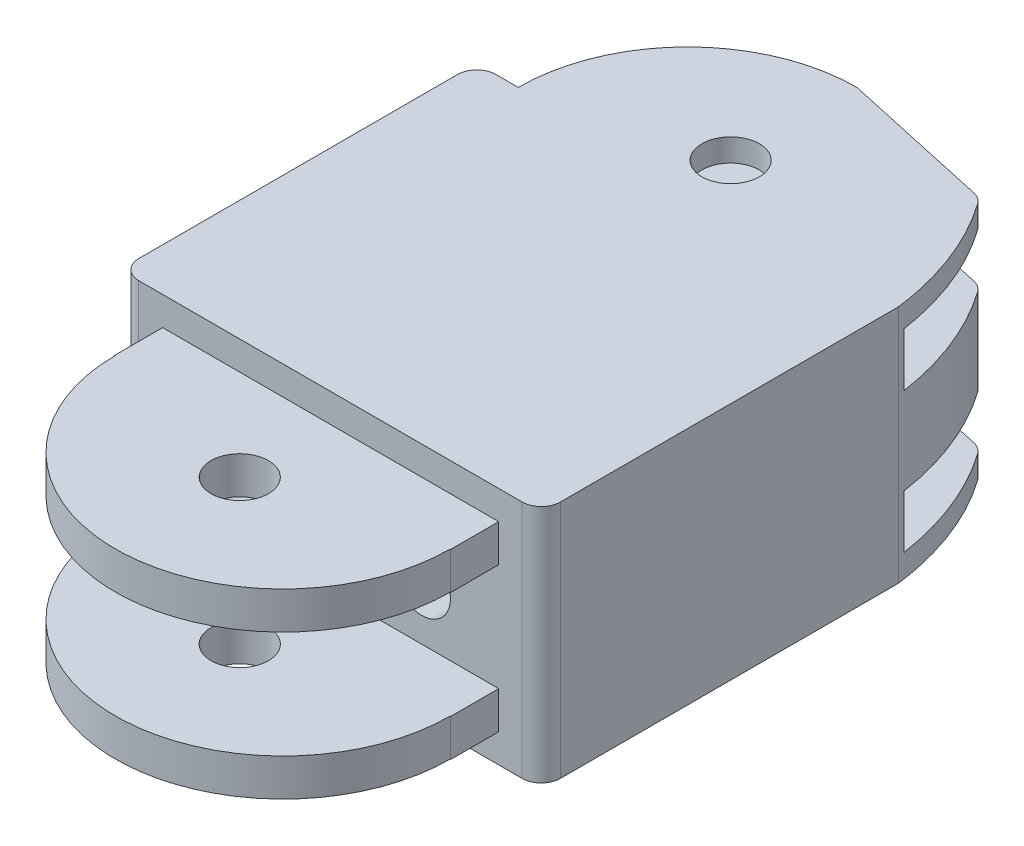
SolidWorks part; units mm, degrees
ref_plane "Front Plane" through (0, 0, 0) normal (0, 0, 1) x (1, 0, 0)
ref_plane "Top Plane" through (0, 0, 0) normal (0, 1, 0) x (1, 0, 0)
ref_plane "Right Plane" through (0, 0, 0) normal (1, 0, 0) x (0, 0, -1)
sketch "Sketch2" plane through (0, 0, 0) normal (0, 0, 1) x (1, 0, 0)
  line L0 (-24.2561, -24.0702) -> (-22.0061, -24.0702) construction
  line L1 (-24.2561, -17.8202) -> (-2.2017, -17.8202) construction
  line L2 (-24.2561, -17.8202) -> (-24.2561, -30.3202) construction
  line L3 (-24.2561, -30.3202) -> (-2.2017, -30.3202) construction
  line L4 (-2.2017, -17.8202) -> (-2.2017, -30.3202) construction
  line L5 (-2.2017, -24.0702) -> (-4.4517, -24.0702) construction
  line L6 (-22.0061, -24.0702) -> (-22.0061, -30.3202) construction
  line L7 (-4.4517, -24.0702) -> (-4.4517, -30.3202) construction
  line L8 (-24.2561, -17.8202) -> (-24.2561, -19.3148) construction
  line L9 (-24.2561, -19.3148) -> (-22.0061, -19.3148) construction
  line L10 (-2.2017, -17.8202) -> (-2.2017, -19.3148) construction
  line L11 (-2.2017, -19.3148) -> (-4.4517, -19.3148) construction
  line L12 (-2.2017, -30.3202) -> (-2.2017, -28.8202) construction
  line L13 (-2.2017, -28.8202) -> (-4.4517, -28.8202) construction
  line L14 (-24.2561, -30.3202) -> (-24.2561, -28.8202) construction
  line L15 (-24.2561, -28.8202) -> (-22.0061, -28.8202) construction
  line L17 (-22.0061, -28.8202) -> (-4.4517, -28.8202)
  line L18 (-22.0061, -28.8202) -> (-22.0061, -26.8702)
  line L19 (-22.0061, -26.8702) -> (-4.4517, -26.8702)
  line L20 (-4.4517, -28.8202) -> (-4.4517, -26.8702)
  line L21 (-22.0061, -28.8202) -> (-4.4517, -26.8702) construction
  line L22 (-22.0061, -26.8702) -> (-4.4517, -28.8202) construction
  line L23 (-22.0061, -19.3148) -> (-4.4517, -19.3148)
  line L24 (-22.0061, -19.3148) -> (-22.0061, -21.2648)
  line L25 (-22.0061, -21.2648) -> (-4.4517, -21.2648)
  line L26 (-4.4517, -19.3148) -> (-4.4517, -21.2648)
  line L27 (-22.0061, -19.3148) -> (-4.4517, -21.2648) construction
  line L28 (-22.0061, -21.2648) -> (-4.4517, -19.3148) construction
  point P19 (-13.2289, -27.8452)
  point P22 (-13.2289, -20.2898)
extrude "Boss-Extrude1" add sketch "Sketch2" along normal blind 8.75
sketch "Sketch3" plane through (0, -19.3148, 0) normal (0, 1, 0) x (1, 0, 0)
  line L0 (-4.4517, 0) -> (-22.0061, 0) construction
  line L1 (-4.4517, -8.75) -> (-22.0061, -8.75) construction
  arc A0 (-13.2289, -8.75) -> (-4.4789, 0) centre (-13.2289, 0) ccw
  arc A1 (-13.2289, -8.75) -> (-21.9789, 0) centre (-13.2289, 0) cw
  spline S0 degree 2 poles (-22.0061, -8.75) (-13.2289, -12.4735) (-4.4517, -8.75) knots 0 0 0 1 1 1
  spline S1 degree 2 poles (-21.9789, 0) (-25.927, -4.2429) (-22.0061, -8.75) knots 0 0 0 1 1 1
  spline S2 degree 2 poles (-4.4789, 0) (1.1383, -4.1517) (-4.4517, -8.75) knots 0 0 0 1 1 1
extrude "Cut-Extrude1" cut sketch "Sketch3" against normal through all contours S0 S2 A0 A1 S1
sketch "Sketch4" plane through (0, 0, 0) normal (0, 0, -1) x (-1, 0, 0)
  line L0 (22.0061, -19.3148) -> (24.2561, -19.3148) construction
  line L1 (22.0061, -19.3148) -> (4.4789, -19.3148) construction
  line L2 (22.0061, -19.3148) -> (22.0061, -28.8202) construction
  line L3 (22.0061, -28.8202) -> (4.4789, -28.8202) construction
  line L4 (4.4789, -19.3148) -> (4.4789, -28.8202) construction
  line L5 (22.0061, -19.3148) -> (4.4789, -28.8202) construction
  line L6 (22.0061, -28.8202) -> (4.4789, -19.3148) construction
  line L7 (24.2561, -19.3148) -> (24.2561, -17.8148) construction
  line L8 (4.4789, -28.8202) -> (2.2289, -28.8202) construction
  line L9 (2.2289, -28.8202) -> (2.2289, -30.3202) construction
  line L11 (24.2561, -17.8148) -> (2.2289, -17.8148)
  line L12 (24.2561, -17.8148) -> (24.2561, -30.3202)
  line L13 (24.2561, -30.3202) -> (2.2289, -30.3202)
  line L14 (2.2289, -17.8148) -> (2.2289, -30.3202)
  line L15 (24.2561, -17.8148) -> (2.2289, -30.3202) construction
  line L16 (24.2561, -30.3202) -> (2.2289, -17.8148) construction
  point P4 (13.2425, -24.0675)
  point P14 (13.2425, -24.0675)
extrude "Boss-Extrude2" add sketch "Sketch4" along normal blind 30 contours L12 L13 L14 L11
sketch "Sketch5" plane through (0, -19.3148, 0) normal (0, 1, 0) x (1, 0, 0)
  line L0 (-13.2289, -8.75) -> (-13.2289, -2.25) construction
  arc A0 (-21.9789, 0) -> (-4.4789, 0) centre (-13.2289, 0) ccw construction
  circle A1 centre (-13.2289, -2.25) radius 1.5
extrude "Cut-Extrude2" cut sketch "Sketch5" against normal blind 12 contours A1
sketch "Sketch6" plane through (0, 0, 0) normal (0, 0, 1) x (1, 0, 0)
  line L0 (-24.2561, -30.3202) -> (-2.2289, -30.3202)
  line L1 (-2.2289, -30.3202) -> (-2.2289, -17.8148)
  line L2 (-2.2289, -17.8148) -> (-24.2561, -17.8148)
  line L3 (-24.2561, -17.8148) -> (-24.2561, -30.3202)
  line L4 (-22.0061, -28.8202) -> (-4.4517, -28.8202)
  line L5 (-4.4517, -28.8202) -> (-4.4517, -26.8702)
  line L6 (-4.4517, -28.8202) -> (-4.4517, -26.8702) construction
  line L7 (-4.4517, -26.8702) -> (-22.0061, -26.8702)
  line L8 (-22.0061, -28.8202) -> (-22.0061, -26.8702)
  line L9 (-22.0061, -21.2648) -> (-22.0061, -19.3148)
  line L10 (-22.0061, -19.3148) -> (-4.4517, -19.3148)
  line L11 (-4.4517, -19.3148) -> (-4.4517, -21.2648)
  line L12 (-4.4517, -21.2648) -> (-22.0061, -21.2648)
extrude "Cut-Extrude3" cut sketch "Sketch6" against normal blind 2.5
sketch "Sketch7" plane through (0, -17.8148, 0) normal (0, 1, 0) x (1, 0, 0)
  line L0 (-13.2425, 30) -> (-13.2425, 23.4057) construction
  line L1 (-24.2561, 30) -> (-2.2289, 30) construction
  line L2 (-13.2425, 23.4057) -> (-13.2425, 21.1557) construction
  line L3 (-22.0869, 21.1557) -> (-24.2561, 21.1557)
  line L4 (-24.2561, 30) -> (-24.2561, 2.5) construction
  line L6 (-2.2289, 30) -> (-2.2289, 2.5) construction
  line L7 (-13.2425, 30) -> (-5.0463, 28.2017)
  circle A0 centre (-13.2425, 23.4057) radius 1.5
  arc A1 (-13.2425, 30) -> (-22.0869, 21.1557) centre (-13.2425, 21.1557) ccw
  spline S0 degree 3 poles (-2.2289, 21.1557) (11.4715, 27.1897) (-11.7652, 53.4313) (-37.0079, 21.5236) (-24.2561, 21.1557) knots 0 0 0 0 0.520113 1 1 1 1
  spline S1 degree 2 poles (-5.0463, 28.2017) (-2.7315, 25.0686) (-2.2289, 21.1557) knots 0 0 0 1 1 1
extrude "Cut-Extrude4" cut sketch "Sketch7" against normal blind 13
sketch "Sketch8" plane through (0, 0, -2.5) normal (0, 0, 1) x (1, 0, 0)
  line L0 (-24.2561, -24.0675) -> (-18.0111, -24.0675) construction
  line L1 (-24.2561, -17.8148) -> (-24.2561, -30.3202) construction
  line L2 (-2.2289, -24.0675) -> (-8.474, -24.0675) construction
  line L3 (-2.2289, -30.3202) -> (-2.2289, -17.8148) construction
  line L4 (-4.4517, -21.2648) -> (-4.4517, -24.0675) construction
  line L5 (-4.4517, -24.0675) -> (-8.474, -24.0675) construction
  circle A0 centre (-18.0111, -24.0675) radius 1.5
  circle A1 centre (-8.474, -24.0675) radius 1.5
extrude "Cut-Extrude5" cut sketch "Sketch8" against normal blind 28
fillet "Fillet3" radius 1 4 edges at (-24.2561, -24.0675, -2.5) (-24.2561, -24.0675, -21.1557) (-2.2289, -24.0675, -2.5) (-5.0463, -24.0675, -28.2017)
ref_plane "Plane4" through (0, 0, -32.5) normal (0, 0, 1) x (1, 0, 0)
sketch "Sketch9" plane through (0, 0, -32.5) normal (0, 0, 1) x (1, 0, 0)
  line L0 (-24.254, -17.8228) -> (-24.254, -19.0025) construction
  line L1 (-24.254, -17.8228) -> (-2.231, -17.8228) construction
  line L2 (-24.254, -17.8228) -> (-24.254, -30.3121) construction
  line L3 (-24.254, -30.3121) -> (-2.231, -30.3121) construction
  line L4 (-2.231, -17.8228) -> (-2.231, -30.3121) construction
  line L5 (-24.254, -17.8228) -> (-2.231, -30.3121) construction
  line L6 (-24.254, -30.3121) -> (-2.231, -17.8228) construction
  line L7 (-24.254, -30.3121) -> (-24.254, -29.1182) construction
  line L8 (-24.254, -19.0025) -> (-2.231, -19.0025)
  line L9 (-24.254, -19.0025) -> (-24.254, -21.7989)
  line L10 (-24.254, -21.7989) -> (-2.231, -21.7989)
  line L11 (-2.231, -19.0025) -> (-2.231, -21.7989)
  line L12 (-24.254, -19.0025) -> (-2.231, -21.7989) construction
  line L13 (-24.254, -21.7989) -> (-2.231, -19.0025) construction
  line L14 (-13.2425, -24.0675) -> (-13.2425, -26.3361) construction
  line L15 (-24.254, -29.1182) -> (-2.231, -29.1182)
  line L16 (-24.254, -29.1182) -> (-24.254, -26.3361)
  line L17 (-24.254, -26.3361) -> (-2.231, -26.3361)
  line L18 (-2.231, -29.1182) -> (-2.231, -26.3361)
  line L19 (-24.254, -29.1182) -> (-2.231, -26.3361) construction
  line L20 (-24.254, -26.3361) -> (-2.231, -29.1182) construction
  line L21 (-13.2425, -21.7989) -> (-13.2425, -24.0675) construction
  point P4 (-13.2425, -24.0675)
  point P8 (-13.2425, -20.4007)
  point P13 (-13.2425, -27.7271)
  point P17 (0, 0)
  point P18 (0, 0)
  point P19 (-24.2683, -29.1182)
  point P20 (0, 0)
  point P22 (-24.254, -19.0025)
extrude "Cut-Extrude6" cut sketch "Sketch9" along normal blind 11
sketch "Sketch10" plane through (0, 0, -21.5) normal (0, 0, -1) x (-1, 0, 0)
  line L0 (22.0802, -21.7989) -> (2.2769, -21.7989) construction
  line L1 (22.0802, -19.0025) -> (4.1279, -19.0025)
  line L2 (22.0802, -19.0025) -> (22.0802, -21.7989)
  line L3 (22.0802, -21.7989) -> (4.1279, -21.7989)
  line L4 (4.1279, -19.0025) -> (4.1279, -21.7989)
  line L5 (22.0802, -19.0025) -> (4.1279, -21.7989) construction
  line L6 (22.0802, -21.7989) -> (4.1279, -19.0025) construction
  line L7 (22.0802, -29.1182) -> (2.2769, -29.1182) construction
  line L8 (22.0802, -26.3361) -> (4.1279, -26.3361)
  line L9 (22.0802, -26.3361) -> (22.0802, -29.1182)
  line L10 (22.0802, -29.1182) -> (4.1279, -29.1182)
  line L11 (4.1279, -26.3361) -> (4.1279, -29.1182)
  line L12 (22.0802, -26.3361) -> (4.1279, -29.1182) construction
  line L13 (22.0802, -29.1182) -> (4.1279, -26.3361) construction
  point P4 (13.104, -20.4007)
  point P12 (13.104, -27.7271)
extrude "Cut-Extrude7" cut sketch "Sketch10" against normal blind 5
